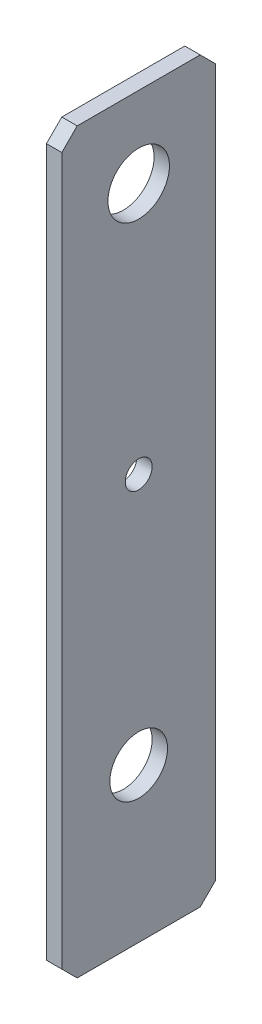
SolidWorks part; units mm, degrees
ref_plane "Front Plane" through (0, 0, 0) normal (0, 0, 1) x (1, 0, 0)
ref_plane "Top Plane" through (0, 0, 0) normal (0, 1, 0) x (1, 0, 0)
ref_plane "Right Plane" through (0, 0, 0) normal (1, 0, 0) x (0, 0, -1)
sketch "Sketch1" plane through (0, 0, 0) normal (1, 0, 0) x (0, 0, -1)
  line L1 (0, 0) -> (20, 0)
  line L2 (0, 0) -> (0, 96)
  line L3 (0, 96) -> (20, 96)
  line L4 (20, 0) -> (20, 96)
  dimension "D1" = 96
  dimension "D2" = 20
extrude "Boss-Extrude1" add sketch "Sketch1" along normal blind 2
sketch "Sketch2" plane through (2, 0, 0) normal (1, 0, 0) x (0, 0, -1)
  line L0 (10, 96) -> (10, 0) construction
  line L1 (20, 96) -> (0, 96) construction
  line L2 (0, 0) -> (20, 0) construction
  circle A0 centre (10, 85.5) radius 4
  circle A1 centre (10, 52.75) radius 1.75
  circle A2 centre (10, 20) radius 3.75
  dimension "D1" = 7.5
  dimension "D2" = 3.5
  dimension "D3" = 8
  dimension "D5" = 32.75
  dimension "D6" = 10.5
  dimension "D4" = 20
extrude "Cut-Extrude1" cut sketch "Sketch2" against normal blind 2
chamfer "Chamfer1" distance 2 angle 45 4 edges at (1, 0, -20) (1, 0, 0) (1, 96, -20) (1, 96, 0)
